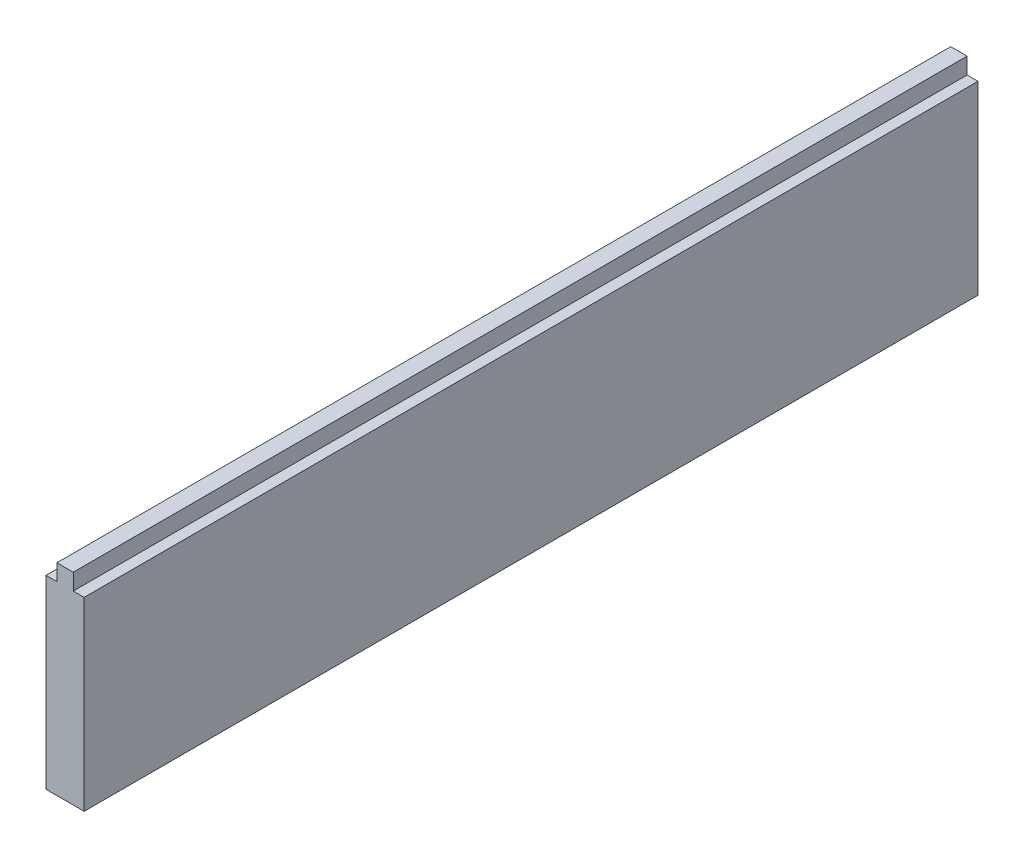
SolidWorks part; units mm, degrees
material "Сосна"
ref_plane "Спереди" through (0, 0, 0) normal (0, 0, 1) x (1, 0, 0)
ref_plane "Сверху" through (0, 0, 0) normal (0, 1, 0) x (1, 0, 0)
ref_plane "Справа" through (0, 0, 0) normal (1, 0, 0) x (0, 0, -1)
sketch "Эскиз1" plane through (0, 0, 0) normal (0, 0, 1) x (1, 0, 0)
  line L0 (0, 0) -> (0, 170)
  line L1 (35, 170) -> (25, 170)
  line L2 (35, 170) -> (35, 0)
  line L3 (0, 0) -> (35, 0)
  line L8 (25, 170) -> (25, 185)
  line L9 (25, 185) -> (10, 185)
  line L10 (10, 185) -> (10, 170)
  line L11 (10, 170) -> (0, 170)
  dimension "D1" = 170
  dimension "D2" = 35
  dimension "D3" = 10
  dimension "D4" = 15
extrude "Бобышка-Вытянуть1" add sketch "Эскиз1" against normal blind 820
